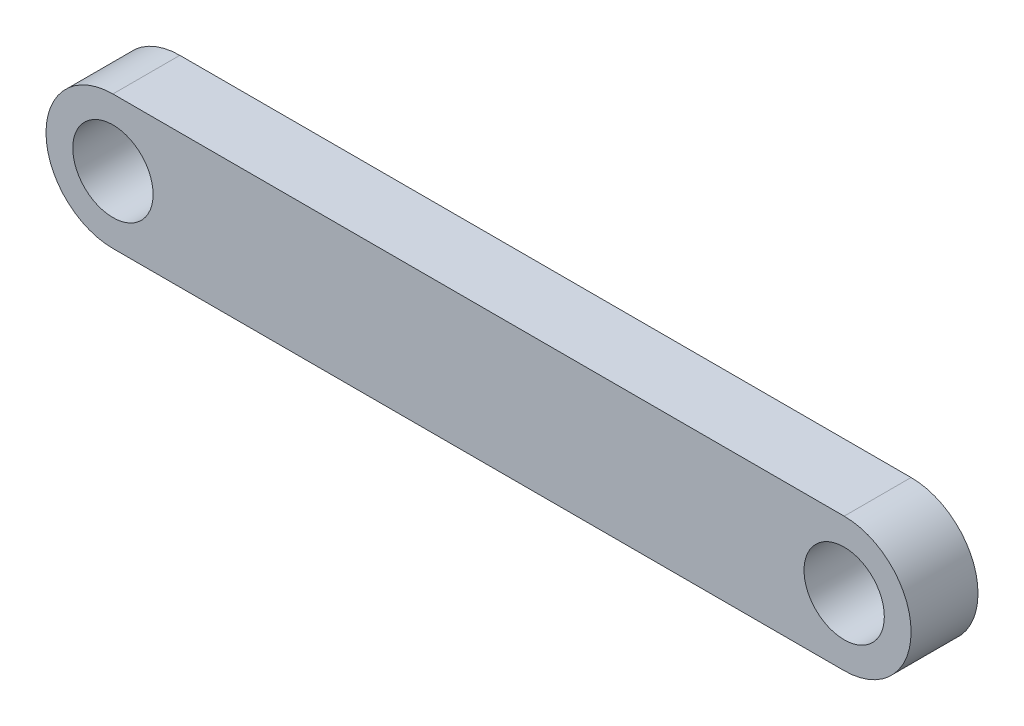
SolidWorks part; units mm, degrees
ref_plane "Plano frontal" through (0, 0, 0) normal (0, 0, 1) x (1, 0, 0)
ref_plane "Plano superior" through (0, 0, 0) normal (0, 1, 0) x (1, 0, 0)
ref_plane "Plano direito" through (0, 0, 0) normal (1, 0, 0) x (0, 0, -1)
sketch "Esboço1" plane through (0, 0, 0) normal (0, 0, 1) x (1, 0, 0)
  line L0 (-27.3185, 5) -> (27.3185, 5)
  line L1 (-5.5882, 0) -> (5.5882, 0) construction
  line L2 (-27.3185, -5) -> (27.3185, -5)
  arc A0 (-27.3185, 5) -> (-27.3185, -5) centre (-27.3185, 0) ccw
  arc A1 (27.3185, 5) -> (27.3185, -5) centre (27.3185, 0) cw
  circle A2 centre (-27.3185, 0) radius 3
  circle A3 centre (27.3185, 0) radius 3
  point P3 (0, 5)
  dimension "D1" = 5
  dimension "D2" = 54.637
extrude "Ressalto-extrusão1" add sketch "Esboço1" along normal blind 5
